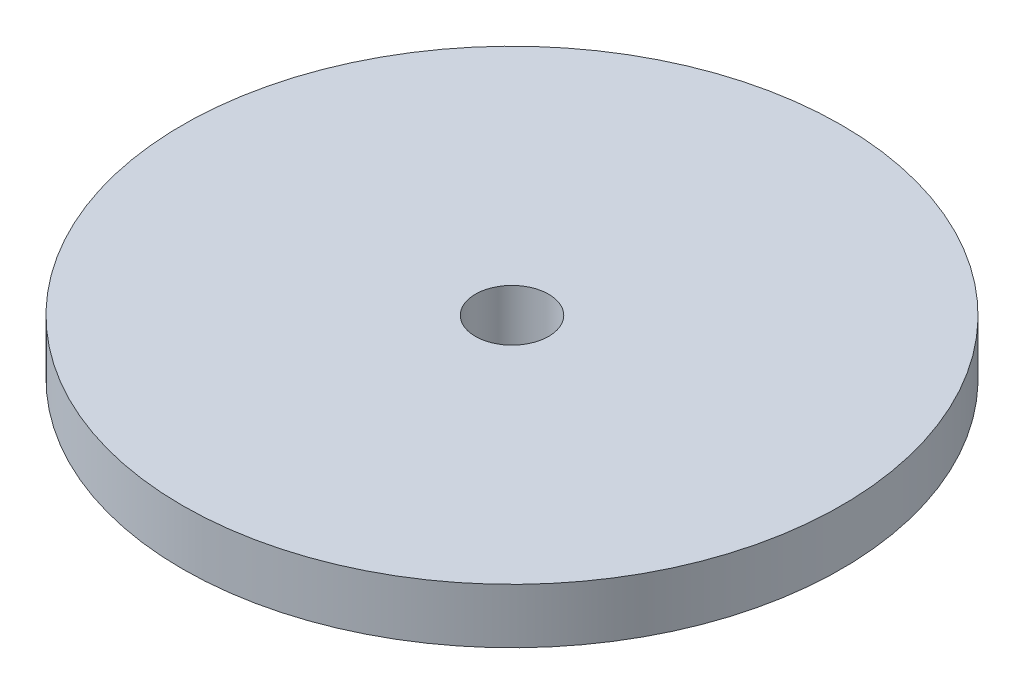
SolidWorks part; units mm, degrees
ref_plane "Front Plane" through (0, 0, 0) normal (0, 0, 1) x (1, 0, 0)
ref_plane "Top Plane" through (0, 0, 0) normal (0, 1, 0) x (1, 0, 0)
ref_plane "Right Plane" through (0, 0, 0) normal (1, 0, 0) x (0, 0, -1)
sketch "Sketch1" plane through (0, 0, 0) normal (0, 1, 0) x (1, 0, 0)
  circle A0 centre (0, 0) radius 90
  circle A1 centre (0, 0) radius 10
  dimension "D1" = 180
  dimension "D2" = 20
extrude "Boss-Extrude1" add sketch "Sketch1" along normal blind 15
